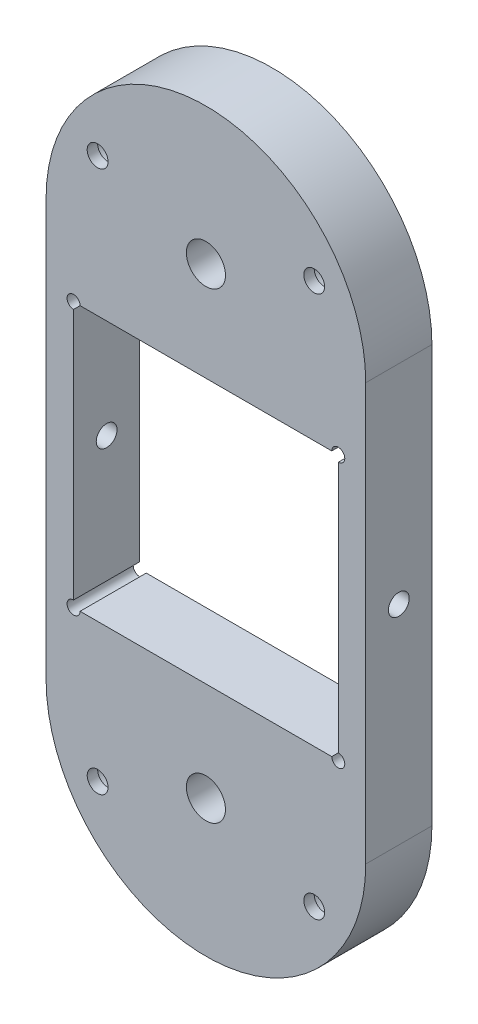
SolidWorks part; units mm, degrees
material "6061-T6 (SS)"
ref_plane "Front Plane" through (0, 0, 0) normal (0, 0, 1) x (1, 0, 0)
ref_plane "Top Plane" through (0, 0, 0) normal (0, 1, 0) x (1, 0, 0)
ref_plane "Right Plane" through (0, 0, 0) normal (1, 0, 0) x (0, 0, -1)
sketch "Sketch1" plane through (0, 0, 0) normal (0, 0, 1) x (1, 0, 0)
  line L2 (0, 62.9125) -> (0, -62.9125) construction
  line L3 (-30.675, 0) -> (30.675, 0) construction
  line L4 (0, -25.4) -> (0, -75) construction
  line L5 (25.4, -25.4) -> (-25.4, -25.4) construction
  line L6 (25.4, -25.4) -> (25.4, 25.4) construction
  line L7 (25.4, 25.4) -> (-25.4, 25.4) construction
  line L8 (-25.4, -25.4) -> (-25.4, 25.4) construction
  line L9 (25.4, -25.4) -> (-25.4, 25.4) construction
  line L10 (25.4, 25.4) -> (-25.4, -25.4) construction
  line L11 (30.675, 40) -> (30.675, -40)
  line L13 (-30.675, -40) -> (-30.675, 40)
  circle A2 centre (0, -40) radius 27.5
  circle A3 centre (0, 40) radius 27.5
  circle A4 centre (18.175, 0) radius 2.5 construction
  circle A5 centre (-18.175, 0) radius 2.5 construction
  arc A6 (30.675, 40) -> (-30.675, 40) centre (0, 40) ccw
  arc A7 (-30.675, -40) -> (30.675, -40) centre (0, -40) ccw
  point P8 (0, 0)
  point P18 (0, 0)
  dimension "D4" = 55
  dimension "D5" = 5
  dimension "D1" = 80
  dimension "D6" = 50.8
  dimension "D7" = 50.8
  dimension "D2" = 61.35
extrude "Boss-Extrude1" add sketch "Sketch1" along normal blind 12.7
sketch "Sketch2" plane through (0, 0, 12.7) normal (0, 0, 1) x (1, 0, 0)
  line L0 (-30.675, 0) -> (30.675, 0) construction
  line L1 (-30.675, 40) -> (-30.675, -40) construction
  line L2 (30.675, -40) -> (30.675, 40) construction
  line L3 (0, 67.5) -> (0, 12.5) construction
  line L4 (-30.675, 40) -> (-30.675, -40)
  line L5 (30.675, -40) -> (30.675, 40)
  circle A2 centre (0, 40) radius 27.5 construction
  arc A4 (30.675, 40) -> (-30.675, 40) centre (0, 40) ccw
  arc A5 (-30.675, -40) -> (30.675, -40) centre (0, -40) ccw
  circle A6 centre (0, 40) radius 24 construction
  circle A7 centre (0, 64) radius 2 construction
  circle A8 centre (20.7846, 52) radius 2
  circle A9 centre (20.7846, 28) radius 2 construction
  circle A10 centre (0, 16) radius 2 construction
  circle A11 centre (-20.7846, 28) radius 2 construction
  circle A12 centre (-20.7846, 52) radius 2
  circle A13 centre (0, -40) radius 24 construction
  circle A14 centre (-20.7846, -52) radius 2
  circle A15 centre (-20.7846, -28) radius 2 construction
  circle A16 centre (0, -16) radius 2 construction
  circle A17 centre (20.7846, -28) radius 2 construction
  circle A18 centre (20.7846, -52) radius 2
  circle A19 centre (0, -64) radius 2 construction
  point P25 (0, 40)
  point P37 (0, -40)
  dimension "D3" = 48
  dimension "D4" = 4
  dimension "D5" = 6
extrude "Boss-Extrude2" add sketch "Sketch2" against normal up to surface (12.7 mm away) up to face at (0, 0, 0)
sketch "Sketch7" plane through (-30.675, 0, 0) normal (-1, 0, 0) x (0, 0, 1)
  line L0 (6.35, 10.2) -> (6.35, -10.2) construction
  line L1 (0, 0) -> (12.7, 0) construction
  line L2 (12.7, 40) -> (12.7, -40) construction
  circle A0 centre (6.35, 0) radius 2
  point P9 (6.35, 0)
  dimension "D1" = 4
extrude "Cut-Extrude4" cut sketch "Sketch7" against normal blind 85
sketch "Sketch8" plane through (0, 0, 12.7) normal (0, 0, 1) x (1, 0, 0)
  line L0 (0, 0) -> (0, 44.4) construction
  line L1 (-25.4, -25.4) -> (25.4, -25.4)
  line L2 (-25.4, -25.4) -> (-25.4, 25.4)
  line L3 (-25.4, 25.4) -> (25.4, 25.4)
  line L4 (25.4, -25.4) -> (25.4, 25.4)
  line L5 (-25.4, -25.4) -> (25.4, 25.4) construction
  line L6 (-25.4, 25.4) -> (25.4, -25.4) construction
  line L7 (-30.675, 0) -> (30.675, 0) construction
  line L8 (-30.675, 40) -> (-30.675, -40) construction
  line L9 (30.675, -40) -> (30.675, 40) construction
  circle A0 centre (0, 44.4) radius 2.5
  circle A1 centre (0, -44.4) radius 2.5
  point P0 (0, 0)
  dimension "D1" = 5
  dimension "D2" = 50.8
  dimension "D3" = 50.8
  dimension "D4" = 19
extrude "Cut-Extrude5" cut sketch "Sketch8" against normal up to surface (12.7 mm away) up to face at (0, 0, 0)
sketch "Sketch9" plane through (0, 0, 0) normal (0, 0, -1) x (-1, 0, 0)
  line L0 (-25.4, 0) -> (25.4, 0) construction
  line L1 (-25.4, 25.4) -> (-25.4, -25.4) construction
  line L2 (25.4, -25.4) -> (25.4, 25.4) construction
  line L3 (25.4, 0) -> (0, 25.4) construction
  line L4 (25.4, 25.4) -> (-25.4, 25.4) construction
  line L5 (0, 25.4) -> (0, -25.4) construction
  line L6 (-25.4, -25.4) -> (25.4, -25.4) construction
  circle A0 centre (-25.4, 25.4) radius 1.25
  circle A1 centre (25.4, 25.4) radius 1.25
  circle A2 centre (25.4, -25.4) radius 1.25
  circle A3 centre (-25.4, -25.4) radius 1.25
  dimension "D1" = 2.5
extrude "Cut-Extrude6" cut sketch "Sketch9" against normal up to surface (12.7 mm away) up to face at (-2.5, -44.4, 12.7)
sketch "Sketch10" plane through (0, 0, 0) normal (0, 0, -1) x (-1, 0, 0)
  line L0 (-30.675, 0) -> (30.675, 0) construction
  line L1 (-30.675, -40) -> (-30.675, 40) construction
  line L2 (30.675, 40) -> (30.675, -40) construction
  line L3 (0, -70.675) -> (0, 70.675) construction
  circle A0 centre (-20.7846, 52) radius 3.75
  arc A1 (-30.675, -40) -> (30.675, -40) centre (0, -40) ccw construction
  arc A2 (30.675, 40) -> (-30.675, 40) centre (0, 40) ccw construction
  circle A3 centre (20.7846, 52) radius 3.75
  circle A4 centre (20.7846, -52) radius 3.75
  circle A5 centre (-20.7846, -52) radius 3.75
  dimension "D1" = 7.5
extrude "Cut-Extrude7" cut sketch "Sketch10" against normal offset from surface (10.7 mm away) 2 up to face at (0, 0, 12.7)
sketch "Sketch11" plane through (0, 0, 12.7) normal (0, 0, 1) x (1, 0, 0)
  line L0 (-25.4, 0) -> (25.4, 0) construction
  line L1 (-25.4, 24.15) -> (-25.4, -24.15) construction
  line L2 (25.4, -24.15) -> (25.4, 24.15) construction
  circle A0 centre (0, 44.4) radius 3.75
  circle A1 centre (0, -44.4) radius 3.75
  dimension "D1" = 7.5
extrude "Cut-Extrude8" cut sketch "Sketch11" against normal offset from surface (10.7 mm away) 2 up to face at (24.5346, -52, 0)
equation "\"d\"=5"
equation "\"D5@Sketch1\"=\"d\""
